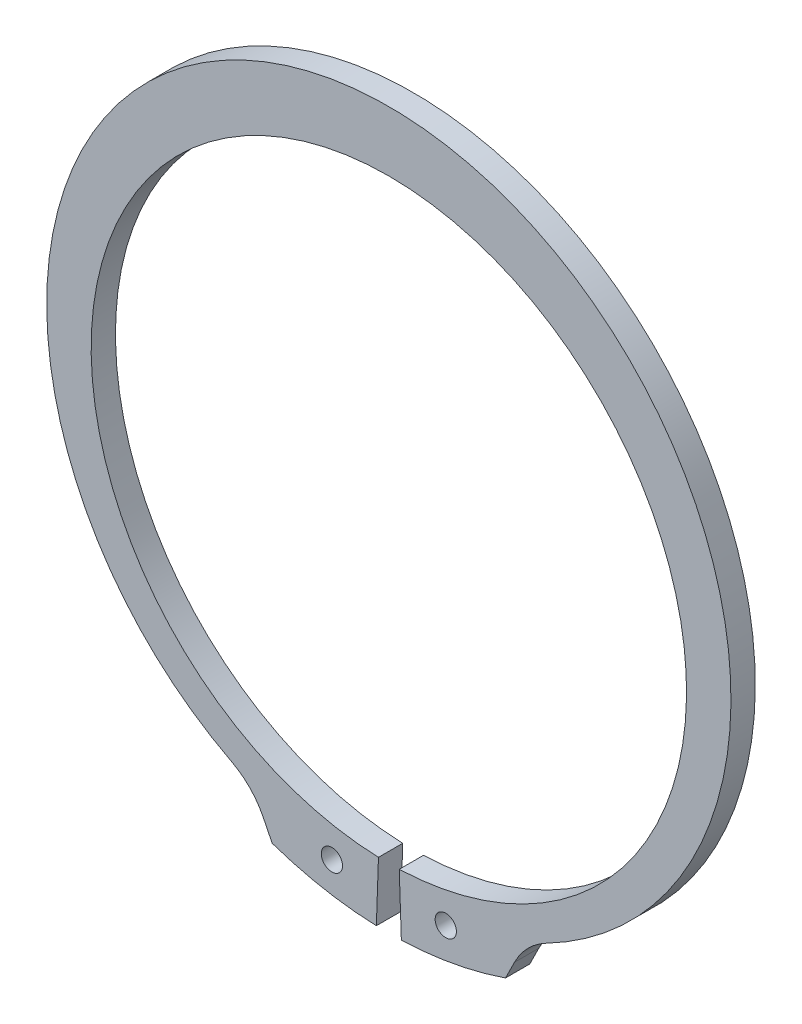
SolidWorks part; units mm, degrees
ref_plane "Front" through (0, 0, 0) normal (0, 0, 1) x (1, 0, 0)
ref_plane "Top" through (0, 0, 0) normal (0, 1, 0) x (1, 0, 0)
ref_plane "Right" through (0, 0, 0) normal (1, 0, 0) x (0, 0, -1)
sketch "Sketch1" plane through (0, 0, 0) normal (0, 0, 1) x (1, 0, 0)
  line L0 (0, 0) -> (-42.4352, -24.5) construction
  line L1 (0, 58.9) -> (0, -58.9) construction
  line L2 (-19.2003, -55.7206) -> (-22.5332, -49.019) construction
  line L4 (-22.5332, -49.019) -> (-24.6006, -53.5165) construction
  line L5 (-22.5332, -49.019) -> (0, 0) construction
  line L6 (0, 49) -> (0, 58.9) construction
  line L7 (0, 58.9) -> (0, 53.95) construction
  line L8 (0, -49) -> (0, -58.9) construction
  line L9 (-8.5088, -48.2556) -> (0, 0) construction
  line L10 (0, 0) -> (-2.0568, -58.9) construction
  line L11 (-19.2003, -55.7206) -> (0, 0) construction
  line L12 (-21.1579, -51.7843) -> (-25.3286, -47.706) construction
  line L13 (-23.2433, -49.7451) -> (-22.5332, -49.019) construction
  line L14 (-8.5088, -48.2556) -> (-10.2341, -58.0405) construction
  line L15 (-9.3714, -53.1481) -> (-7.648, -53.4519) construction
  arc A0 (0, 58.9) -> (-22.5332, -49.019) centre (0, 2.5881) ccw construction
  circle A2 centre (0, 0) radius 58.9 construction
  arc A3 (-19.2003, -55.7206) -> (-2.0568, -58.9) centre (0, 0) ccw construction
  circle A4 centre (0, 0) radius 49 construction
  circle A6 centre (-9.3714, -53.1481) radius 1.75 construction
  arc A7 (-25.3286, -47.706) -> (-21.1579, -51.7843) centre (-29.6607, -56.3079) cw construction
  circle A9 centre (0, 0) radius 52.5 construction
  circle A10 centre (0, 0) radius 50.5 construction
  point P5 (-42.4352, -24.5)
  point P24 (-19.1886, -55.6867)
  point P35 (0, 58.9)
  point P36 (0, 49)
  point P37 (0, -49)
  point P38 (0, -58.9)
  dimension "Hole Diameter" = 3.5
  dimension "D10" = 9.6312
  dimension "For OD" = 105
  dimension "For Groove Diameter" = 101
  dimension "Ring ID" = 98
  dimension "Max Sec." = 9.9
  dimension "Lug Height" = 9.9
  dimension "D6" = 2
  dimension "D5" = 7.4847
  dimension "D8" = 5.8333
  dimension "D3" = 120
  dimension "D7" = 8
  dimension "D2" = 17.5
  dimension "D4" = 5.8333
sketch "Sketch2" plane through (0, 0, 0) normal (-1, 0, 0) x (0, 1, 0)
  line L0 (-58.9, 2) -> (-58.9, -2) construction
  line L1 (58.9, -2.075) -> (58.9, 2.075) construction
  line L2 (0, 2) -> (0, -2) construction
  line L4 (-58.9, 0) -> (58.9, 0) construction
  point P3 (-58.9, 0)
  point P6 (0, 0)
  point P14 (58.9, 0)
  dimension "Ring Thickness" = 4
  dimension "For Groove Width" = 4.15
sketch "Sketch4" plane through (0, 0, 0) normal (0, 0, 1) x (1, 0, 0)
  line L0 (-19.2003, -55.7206) -> (-22.5332, -49.019) construction
  line L1 (-19.2003, -55.7206) -> (-22.5332, -49.019)
  line L2 (0, 58.9) -> (0, 49)
  line L3 (-2.0568, -58.9) -> (-1.7101, -48.9702)
  line L4 (0, 0) -> (-2.0568, -58.9) construction
  arc A0 (0, 58.9) -> (-22.5332, -49.019) centre (0, 2.5881) ccw construction
  arc A1 (-19.2003, -55.7206) -> (-2.0568, -58.9) centre (0, 0) ccw construction
  circle A2 centre (-9.3714, -53.1481) radius 1.75 construction
  arc A4 (0, 58.9) -> (-22.5332, -49.019) centre (0, 2.5881) ccw
  arc A5 (-19.2003, -55.7206) -> (-2.0568, -58.9) centre (0, 0) ccw
  circle A6 centre (-9.3714, -53.1481) radius 1.75
  circle A7 centre (0, 0) radius 49 construction
  arc A8 (0, 49) -> (-1.7101, -48.9702) centre (0, 0) ccw
extrude "Boss-Extrude1" add sketch "Sketch4" along normal mid plane 4
fillet "Fillet1" radius 12.039 1 edges at (-22.5332, -49.019, 0)
sketch "Sketch5" [suppressed] plane through (0, 0, 0) normal (0, 0, 1) x (1, 0, 0)
  line L0 (0, 39.75) -> (0, 0) construction
  line L1 (0, 0) -> (-23.1297, 40.0617) construction
  line L2 (-23.1297, 40.0617) -> (-23.6297, 40.9278)
  arc A0 (0, 39.75) -> (-1.3873, -39.7258) centre (0, 0) ccw construction
  arc A1 (0, 47.55) -> (-24.824, -36.0138) centre (0, 2.0809) ccw construction
  arc A2 (-23.1297, 40.0617) -> (-45.4214, 0) centre (-1.8633, 1.9956) ccw
  arc A3 (-23.6297, 40.9278) -> (-45.4214, 0) centre (0, 2.0809) ccw
  dimension "D1" = 30
  dimension "D2" = 1
extrude "Cut-Extrude1" [suppressed] cut sketch "Sketch5" against normal through all both and the other way through all
fillet "Fillet2" [suppressed] radius 1.5
mirror "Mirror1" about plane through (0, 58.9, 2) normal (-1, 0, 0) of bodies 109
sketch "Sketch3" plane through (0, 0, 2) normal (0, 0, 1) x (1, 0, 0)
  line L0 (23.6106, -42.9365) -> (25.9259, -47.4007) construction
  line L1 (25.9259, -47.4007) -> (30.3901, -45.0854) construction
  line L2 (0, 58.9) -> (0, 49) construction
  circle A0 centre (0, 0) radius 49 construction
  arc A1 (25.9259, -47.4007) -> (-25.9259, -47.4007) centre (0, 2.5881) ccw construction
equation "\"D1@Fillet1\"=\"D10@Sketch1\"*1.25"
equation "\"Thickness@Boss-Extrude1\"  = \"Ring Thickness@Sketch5\""
equation "\"D2@Sketch1\"=\"Hole Diameter@Sketch1\"*5"
equation "\"D4@Sketch1\"=\"D2@Sketch1\"/3"
equation "\"D8@Sketch1\"=\"D4@Sketch1\""
